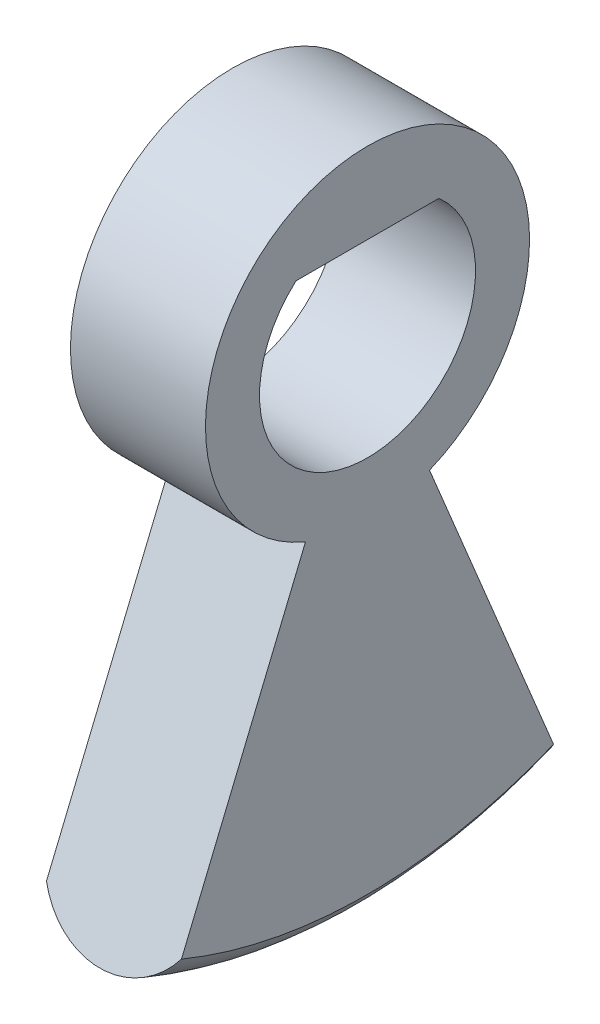
SolidWorks part; units mm, degrees
ref_plane "Front Plane" through (0, 0, 0) normal (0, 0, 1) x (1, 0, 0)
ref_plane "Top Plane" through (0, 0, 0) normal (0, 1, 0) x (1, 0, 0)
ref_plane "Right Plane" through (0, 0, 0) normal (1, 0, 0) x (0, 0, -1)
sketch "Sketch3" plane through (0, 0, 0) normal (0, 0, 1) x (1, 0, 0)
  line L0 (1.25, 0) -> (1.25, 9)
  line L1 (-1.25, 9) -> (-1.25, 0)
  line L2 (-1.25, 0) -> (1.25, 0)
  arc A0 (1.25, 9) -> (-1.25, 9) centre (0, 8.2132) ccw
  point P5 (0, 0)
revolve "Revolve1" add sketch "Sketch3" angle 360 about L2
sketch "Sketch4" plane through (1.25, 0, 0) normal (1, 0, 0) x (0, 0, -1)
  line L0 (1.3229, 1.5) -> (-1.3229, 1.5)
  line L2 (1.118, 1) -> (-1.118, 1)
  arc A0 (-1.118, 1) -> (1.118, 1) centre (0, 0) ccw
  arc A1 (-1.3229, 1.5) -> (1.3229, 1.5) centre (0, 0) ccw
  dimension "D1" = 0.5
extrude "Cut-Extrude1" cut sketch "Sketch4" against normal blind 10 contours L2 A0 | L0 A1 A0 L2
sketch "Sketch7" plane through (0, 0, 0) normal (0, 0, 1) x (1, 0, 0)
  line L0 (0, 0) -> (0, 3)
  line L1 (-1.25, 3) -> (1.25, 3)
  line L2 (-1.25, 9) -> (-1.25, -9) construction
  line L3 (1.25, -9) -> (1.25, 9) construction
  line L4 (1.25, 3) -> (1.25, 9)
  line L6 (-1.25, 9) -> (-1.25, 3)
  line L7 (-1.25, 0) -> (1.25, 0)
  arc A0 (-1.25, 9) -> (1.25, 9) centre (0, 8.2132) cw
revolve "Cut-Revolve1" cut sketch "Sketch7" angle 157.5 about L7 other way angle 157.5
